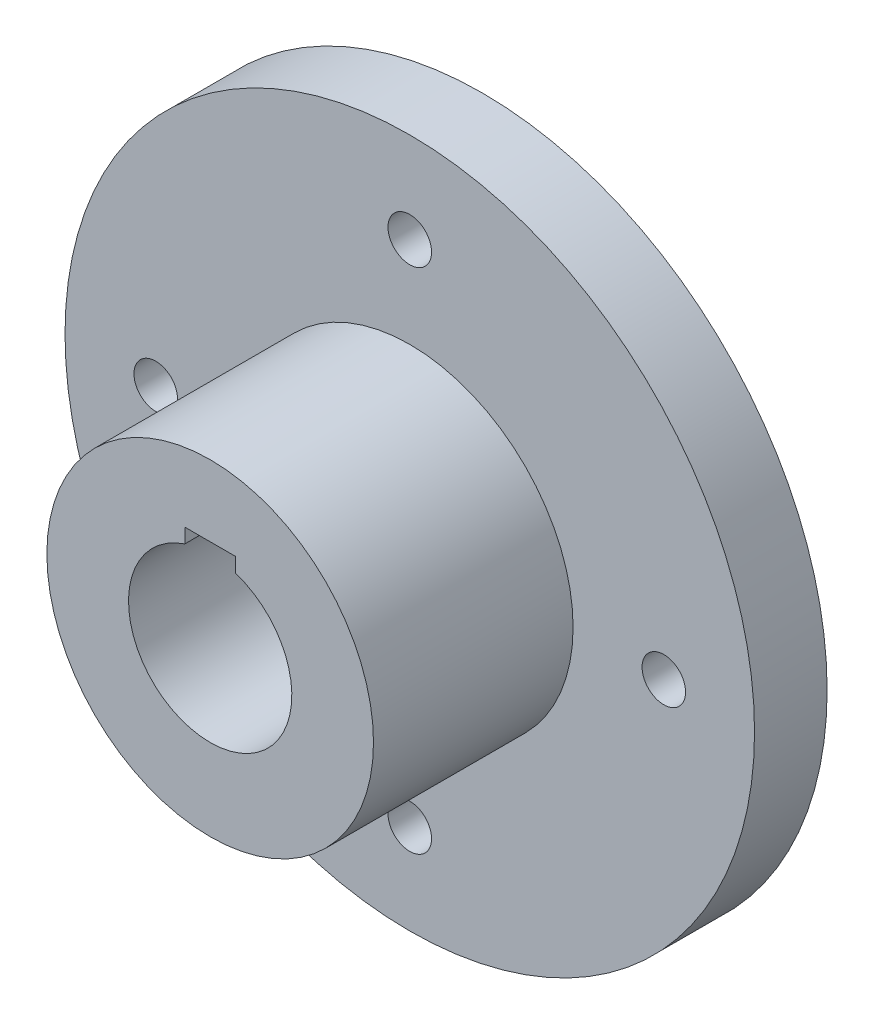
SolidWorks part; units mm, degrees
ref_plane "Front Plane" through (0, 0, 0) normal (0, 0, 1) x (1, 0, 0)
ref_plane "Top Plane" through (0, 0, 0) normal (0, 1, 0) x (1, 0, 0)
ref_plane "Right Plane" through (0, 0, 0) normal (1, 0, 0) x (0, 0, -1)
sketch "Sketch1" plane through (0, 0, 0) normal (0, 0, 1) x (1, 0, 0)
  line L0 (0, 84.2674) -> (0, -63.6938) construction
  line L1 (-83.9856, 0) -> (145.4247, 0) construction
  circle A0 centre (0, 0) radius 95
  dimension "D1" = 190
extrude "Boss-Extrude1" add sketch "Sketch1" along normal blind 20 contours A0
sketch "Sketch2" plane through (0, 0, 0) normal (0, 0, -1) x (-1, 0, 0)
  circle A0 centre (0, 70) radius 6
  circle A1 centre (70, 0) radius 6
  circle A2 centre (0, -70) radius 6
  circle A3 centre (-70, 0) radius 6
extrude "Cut-Extrude1" cut sketch "Sketch2" against normal blind 20
sketch "Sketch3" plane through (0, 0, 0) normal (0, 0, -1) x (-1, 0, 0)
  line L1 (-7, 22.5) -> (-7, 21.3834)
  line L2 (-7, 25.4) -> (7, 25.4)
  line L3 (-7, 25.4) -> (-7, 22.5)
  line L5 (7, 25.4) -> (7, 22.5)
  line L6 (-7, 25.4) -> (7, 22.5) construction
  line L7 (-7, 22.5) -> (7, 25.4) construction
  line L8 (7, 22.5) -> (7, 21.3834)
  arc A0 (-7, 21.3834) -> (7, 21.3834) centre (0, 0) ccw
  point P5 (0, 23.95)
sketch "Sketch5" plane through (0, 0, 20) normal (0, 0, 1) x (1, 0, 0)
  circle A0 centre (0, 0) radius 45
extrude "Boss-Extrude3" add sketch "Sketch5" along normal blind 55
extrude "Cut-Extrude4" cut sketch "Sketch3" against normal blind 75
